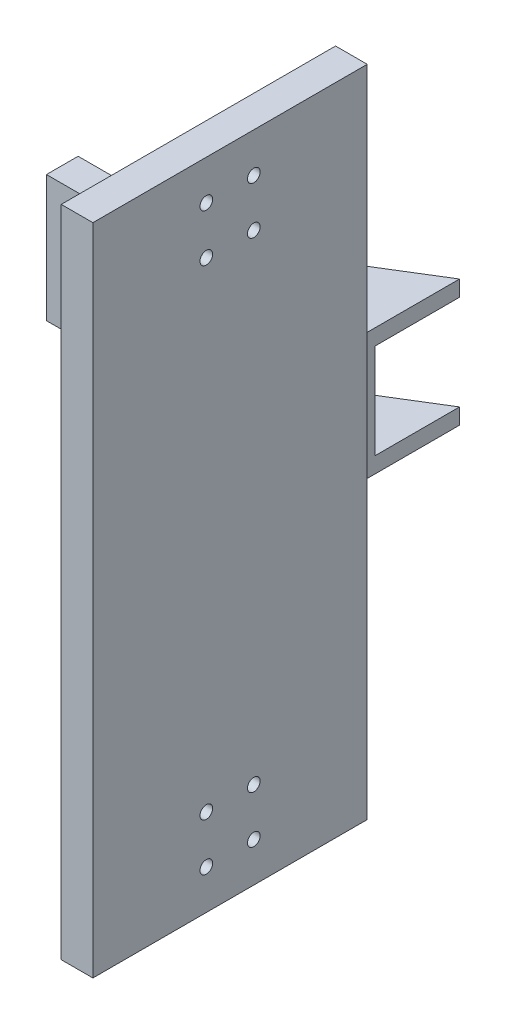
SolidWorks part; units mm, degrees
material "ABS"
ref_plane "Front Plane" through (0, 0, 0) normal (0, 0, 1) x (1, 0, 0)
ref_plane "Top Plane" through (0, 0, 0) normal (0, 1, 0) x (1, 0, 0)
ref_plane "Right Plane" through (0, 0, 0) normal (1, 0, 0) x (0, 0, -1)
ref_plane "P_pelvis_pla" through (-83.5, 0, 0) normal (1, 0, 0) x (0, 0, -1)
sketch "Sketch1" plane through (-83.5, 0, 0) normal (1, 0, 0) x (0, 0, -1)
  line L1 (-26, -62) -> (26, -62)
  line L2 (-26, -62) -> (-26, 62)
  line L3 (-26, 62) -> (26, 62)
  line L4 (26, -62) -> (26, 62)
extrude "Boss-Extrude1" add sketch "Sketch1" along normal blind 6
ref_plane "P_spine_upri" through (0, 0, -33.5) normal (0, 0, 1) x (1, 0, 0)
sketch "Sketch2" plane through (0, 0, -33.5) normal (0, 0, 1) x (1, 0, 0)
  line L0 (-83.5, -41.525) -> (-83.5, 41.525) construction
  line L1 (-139.8, -12) -> (-83.5, -12)
  line L2 (-139.8, -12) -> (-139.8, 12)
  line L3 (-139.8, 12) -> (-83.5, 12)
  line L4 (-83.5, -12) -> (-83.5, 12)
extrude "Boss-Extrude2" add sketch "Sketch2" along normal blind 6
ref_plane "P_gusset_y+9" through (0, 9, 0) normal (0, 1, 0) x (1, 0, 0)
sketch "Sketch3" plane through (0, 9, 0) normal (0, 1, 0) x (1, 0, 0)
  line L0 (-83.5, 33.5) -> (-83.5, 49.5)
  line L1 (-34.265, 33.5) -> (34.265, 33.5) construction
  line L2 (-83.5, 49.5) -> (-109.5, 33.5)
  line L3 (-109.5, 33.5) -> (-83.5, 33.5)
extrude "Boss-Extrude3" add sketch "Sketch3" along normal blind 3
ref_plane "P_gusset_y-1" through (0, -12, 0) normal (0, 1, 0) x (1, 0, 0)
sketch "Sketch4" plane through (0, -12, 0) normal (0, 1, 0) x (1, 0, 0)
  line L0 (-83.5, 33.5) -> (-83.5, 49.5)
  line L1 (-34.265, 33.5) -> (34.265, 33.5) construction
  line L2 (-83.5, -41.525) -> (-83.5, 41.525) construction
  line L3 (-83.5, 49.5) -> (-109.5, 33.5)
  line L4 (-109.5, 33.5) -> (-83.5, 33.5)
extrude "Boss-Extrude4" add sketch "Sketch4" along normal blind 3
hole_wizard "M2 Clearance Hole1" positions "Sketch6" profile "Sketch5" hole size "M2" standard "ISO"
sketch "Sketch6" plane through (-83.5, 0, 0) normal (-1, 0, 0) x (0, 0, 1)
  point P0 (-4.5, 45.5)
sketch "Sketch5" plane through (-83.5, 45.5, -4.5) normal (0, 1, 0) x (0, 0, 1)
  line L0 (0, 0) -> (0, 6)
  line L1 (0, 6) -> (1.2, 6)
  line L2 (1.2, 6) -> (1.2, 0)
  line L5 (1.2, 0) -> (0, 0)
  line L11 (0, -6.35) -> (0, 107.95) construction
  dimension "Thru Hole Dia." = 2.4
  dimension "Thru Hole Depth" = 6
hole_wizard "M2 Clearance Hole2" positions "Sketch8" profile "Sketch7" hole size "M2" standard "ISO"
sketch "Sketch8" plane through (-83.5, 0, 0) normal (-1, 0, 0) x (0, 0, 1)
  point P0 (4.5, 45.5)
sketch "Sketch7" plane through (-83.5, 45.5, 4.5) normal (0, 1, 0) x (0, 0, 1)
  line L0 (0, 0) -> (0, 6)
  line L1 (0, 6) -> (1.2, 6)
  line L2 (1.2, 6) -> (1.2, 0)
  line L5 (1.2, 0) -> (0, 0)
  line L11 (0, -6.35) -> (0, 107.95) construction
  dimension "Thru Hole Dia." = 2.4
  dimension "Thru Hole Depth" = 6
hole_wizard "M2 Clearance Hole3" positions "Sketch10" profile "Sketch9" hole size "M2" standard "ISO"
sketch "Sketch10" plane through (-83.5, 0, 0) normal (-1, 0, 0) x (0, 0, 1)
  point P0 (-4.5, 54.5)
sketch "Sketch9" plane through (-83.5, 54.5, -4.5) normal (0, 1, 0) x (0, 0, 1)
  line L0 (0, 0) -> (0, 6)
  line L1 (0, 6) -> (1.2, 6)
  line L2 (1.2, 6) -> (1.2, 0)
  line L5 (1.2, 0) -> (0, 0)
  line L11 (0, -6.35) -> (0, 107.95) construction
  dimension "Thru Hole Dia." = 2.4
  dimension "Thru Hole Depth" = 6
hole_wizard "M2 Clearance Hole4" positions "Sketch12" profile "Sketch11" hole size "M2" standard "ISO"
sketch "Sketch12" plane through (-83.5, 0, 0) normal (-1, 0, 0) x (0, 0, 1)
  point P0 (4.5, 54.5)
sketch "Sketch11" plane through (-83.5, 54.5, 4.5) normal (0, 1, 0) x (0, 0, 1)
  line L0 (0, 0) -> (0, 6)
  line L1 (0, 6) -> (1.2, 6)
  line L2 (1.2, 6) -> (1.2, 0)
  line L5 (1.2, 0) -> (0, 0)
  line L11 (0, -6.35) -> (0, 107.95) construction
  dimension "Thru Hole Dia." = 2.4
  dimension "Thru Hole Depth" = 6
hole_wizard "M2 Clearance Hole5" positions "Sketch14" profile "Sketch13" hole size "M2" standard "ISO"
sketch "Sketch14" plane through (-83.5, 0, 0) normal (-1, 0, 0) x (0, 0, 1)
  point P0 (-4.5, -54.5)
sketch "Sketch13" plane through (-83.5, -54.5, -4.5) normal (0, 1, 0) x (0, 0, 1)
  line L0 (0, 0) -> (0, 6)
  line L1 (0, 6) -> (1.2, 6)
  line L2 (1.2, 6) -> (1.2, 0)
  line L5 (1.2, 0) -> (0, 0)
  line L11 (0, -6.35) -> (0, 107.95) construction
  dimension "Thru Hole Dia." = 2.4
  dimension "Thru Hole Depth" = 6
hole_wizard "M2 Clearance Hole6" positions "Sketch16" profile "Sketch15" hole size "M2" standard "ISO"
sketch "Sketch16" plane through (-83.5, 0, 0) normal (-1, 0, 0) x (0, 0, 1)
  point P0 (4.5, -54.5)
sketch "Sketch15" plane through (-83.5, -54.5, 4.5) normal (0, 1, 0) x (0, 0, 1)
  line L0 (0, 0) -> (0, 6)
  line L1 (0, 6) -> (1.2, 6)
  line L2 (1.2, 6) -> (1.2, 0)
  line L5 (1.2, 0) -> (0, 0)
  line L11 (0, -6.35) -> (0, 107.95) construction
  dimension "Thru Hole Dia." = 2.4
  dimension "Thru Hole Depth" = 6
hole_wizard "M2 Clearance Hole7" positions "Sketch18" profile "Sketch17" hole size "M2" standard "ISO"
sketch "Sketch18" plane through (-83.5, 0, 0) normal (-1, 0, 0) x (0, 0, 1)
  point P0 (-4.5, -45.5)
sketch "Sketch17" plane through (-83.5, -45.5, -4.5) normal (0, 1, 0) x (0, 0, 1)
  line L0 (0, 0) -> (0, 6)
  line L1 (0, 6) -> (1.2, 6)
  line L2 (1.2, 6) -> (1.2, 0)
  line L5 (1.2, 0) -> (0, 0)
  line L11 (0, -6.35) -> (0, 107.95) construction
  dimension "Thru Hole Dia." = 2.4
  dimension "Thru Hole Depth" = 6
hole_wizard "M2 Clearance Hole8" positions "Sketch20" profile "Sketch19" hole size "M2" standard "ISO"
sketch "Sketch20" plane through (-83.5, 0, 0) normal (-1, 0, 0) x (0, 0, 1)
  point P0 (4.5, -45.5)
sketch "Sketch19" plane through (-83.5, -45.5, 4.5) normal (0, 1, 0) x (0, 0, 1)
  line L0 (0, 0) -> (0, 6)
  line L1 (0, 6) -> (1.2, 6)
  line L2 (1.2, 6) -> (1.2, 0)
  line L5 (1.2, 0) -> (0, 0)
  line L11 (0, -6.35) -> (0, 107.95) construction
  dimension "Thru Hole Dia." = 2.4
  dimension "Thru Hole Depth" = 6
hole_wizard "M2 Clearance Hole9" positions "Sketch22" profile "Sketch21" hole size "M2" standard "ISO"
sketch "Sketch22" plane through (0, 0, -33.5) normal (0, 0, -1) x (-1, 0, 0)
  point P0 (109.3, 4.5)
sketch "Sketch21" plane through (-109.3, 4.5, -33.5) normal (1, 0, 0) x (0, 1, 0)
  line L0 (0, 0) -> (0, 59.5)
  line L1 (0, 59.5) -> (1.2, 59.5)
  line L2 (1.2, 59.5) -> (1.2, 0)
  line L5 (1.2, 0) -> (0, 0)
  line L11 (0, -6.35) -> (0, 107.95) construction
  dimension "Thru Hole Dia." = 2.4
  dimension "Thru Hole Depth" = 59.5
hole_wizard "M2 Clearance Hole10" positions "Sketch24" profile "Sketch23" hole size "M2" standard "ISO"
sketch "Sketch24" plane through (0, 0, -33.5) normal (0, 0, -1) x (-1, 0, 0)
  point P0 (109.3, -4.5)
sketch "Sketch23" plane through (-109.3, -4.5, -33.5) normal (1, 0, 0) x (0, 1, 0)
  line L0 (0, 0) -> (0, 59.5)
  line L1 (0, 59.5) -> (1.2, 59.5)
  line L2 (1.2, 59.5) -> (1.2, 0)
  line L5 (1.2, 0) -> (0, 0)
  line L11 (0, -6.35) -> (0, 107.95) construction
  dimension "Thru Hole Dia." = 2.4
  dimension "Thru Hole Depth" = 59.5
hole_wizard "M2 Clearance Hole11" positions "Sketch26" profile "Sketch25" hole size "M2" standard "ISO"
sketch "Sketch26" plane through (0, 0, -33.5) normal (0, 0, -1) x (-1, 0, 0)
  point P0 (118.3, 4.5)
sketch "Sketch25" plane through (-118.3, 4.5, -33.5) normal (1, 0, 0) x (0, 1, 0)
  line L0 (0, 0) -> (0, 59.5)
  line L1 (0, 59.5) -> (1.2, 59.5)
  line L2 (1.2, 59.5) -> (1.2, 0)
  line L5 (1.2, 0) -> (0, 0)
  line L11 (0, -6.35) -> (0, 107.95) construction
  dimension "Thru Hole Dia." = 2.4
  dimension "Thru Hole Depth" = 59.5
hole_wizard "M2 Clearance Hole12" positions "Sketch28" profile "Sketch27" hole size "M2" standard "ISO"
sketch "Sketch28" plane through (0, 0, -33.5) normal (0, 0, -1) x (-1, 0, 0)
  point P0 (118.3, -4.5)
sketch "Sketch27" plane through (-118.3, -4.5, -33.5) normal (1, 0, 0) x (0, 1, 0)
  line L0 (0, 0) -> (0, 59.5)
  line L1 (0, 59.5) -> (1.2, 59.5)
  line L2 (1.2, 59.5) -> (1.2, 0)
  line L5 (1.2, 0) -> (0, 0)
  line L11 (0, -6.35) -> (0, 107.95) construction
  dimension "Thru Hole Dia." = 2.4
  dimension "Thru Hole Depth" = 59.5
